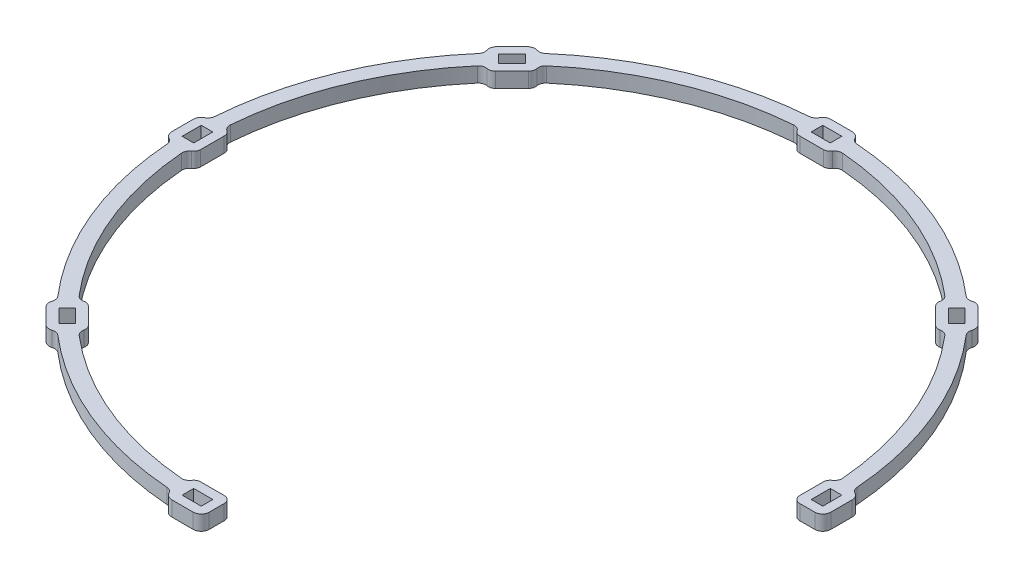
SolidWorks part; units mm, degrees
ref_plane "Front Plane" through (0, 0, 0) normal (0, 0, 1) x (1, 0, 0)
ref_plane "Top Plane" through (0, 0, 0) normal (0, 1, 0) x (1, 0, 0)
ref_plane "Right Plane" through (0, 0, 0) normal (1, 0, 0) x (0, 0, -1)
sketch "Sketch1" plane through (0, 0, 0) normal (0, 1, 0) x (1, 0, 0)
  line L0 (0, 0) -> (2.5, -85.9637) construction
  line L1 (0, 0) -> (85.9637, -2.5) construction
  line L2 (2.3837, -81.9653) -> (2.5, -85.9637)
  line L3 (81.9653, -2.3837) -> (85.9637, -2.5)
  arc A0 (85.9637, -2.5) -> (2.5, -85.9637) centre (0, 0) ccw
  arc A1 (81.9653, -2.3837) -> (2.3837, -81.9653) centre (0, 0) ccw
  dimension "D1" = 172
  dimension "D2" = 4
  dimension "D3" = 2.5
  dimension "D4" = 2.5
extrude "Boss-Extrude1" add sketch "Sketch1" along normal blind 4 contours A1 L2 A0 L3
sketch "Sketch5" plane through (0, 4, 0) normal (0, 1, 0) x (1, 0, 0)
  line L0 (0, -82) -> (0, -86) construction
  line L1 (-61.4104, -54.3393) -> (-64.2439, -57.1728)
  line L2 (-3.1526, -80) -> (3.1526, -80)
  line L3 (-5, -81.8474) -> (-5, -85.8545)
  line L4 (-2.8545, -88) -> (2.8545, -88)
  line L5 (5, -81.8474) -> (5, -85.8545)
  line L6 (-5, -80) -> (5, -88) construction
  line L7 (-5, -88) -> (5, -80) construction
  line L8 (-58.7978, -54.3393) -> (-54.3393, -58.7978)
  line L9 (-54.3393, -61.4104) -> (-57.1728, -64.2439)
  line L10 (-64.2439, -60.2069) -> (-60.2069, -64.2439)
  line L11 (-81.8474, 5) -> (-85.8545, 5)
  line L12 (-80, 3.1526) -> (-80, -3.1526)
  line L13 (-81.8474, -5) -> (-85.8545, -5)
  line L14 (-88, 2.8545) -> (-88, -2.8545)
  line L15 (-54.3393, 61.4104) -> (-57.1728, 64.2439)
  line L16 (-54.3393, 58.7978) -> (-58.7978, 54.3393)
  line L17 (-61.4104, 54.3393) -> (-64.2439, 57.1728)
  line L18 (-60.2069, 64.2439) -> (-64.2439, 60.2069)
  line L19 (5, 81.8474) -> (5, 85.8545)
  line L20 (3.1526, 80) -> (-3.1526, 80)
  line L21 (-5, 81.8474) -> (-5, 85.8545)
  line L22 (2.8545, 88) -> (-2.8545, 88)
  line L23 (61.4104, 54.3393) -> (64.2439, 57.1728)
  line L24 (58.7978, 54.3393) -> (54.3393, 58.7978)
  line L25 (54.3393, 61.4104) -> (57.1728, 64.2439)
  line L26 (64.2439, 60.2069) -> (60.2069, 64.2439)
  line L27 (81.8474, -5) -> (85.8545, -5)
  line L28 (80, -3.1526) -> (80, 3.1526)
  line L29 (81.8474, 5) -> (85.8545, 5)
  line L30 (88, -2.8545) -> (88, 2.8545)
  line L31 (54.3393, -61.4104) -> (57.1728, -64.2439) [skipped]
  line L32 (54.3393, -58.7978) -> (58.7978, -54.3393) [skipped]
  line L33 (61.4104, -54.3393) -> (64.2439, -57.1728) [skipped]
  line L34 (60.2069, -64.2439) -> (64.2439, -60.2069) [skipped]
  line L35 (0, 0) -> (3.1526, -80) construction
  arc A0 (81.9653, -2.3837) -> (2.3837, -81.9653) centre (0, 0) ccw construction
  arc A1 (85.9637, -2.5) -> (2.5, -85.9637) centre (0, 0) ccw construction
  circle A2 centre (0, 0) radius 84 construction
  arc A3 (-5, -85.8545) -> (-2.8545, -88) centre (-2.8545, -85.8545) ccw
  arc A4 (3.1526, -80) -> (5, -81.8474) centre (3.1526, -81.8474) cw
  arc A5 (2.8545, -88) -> (5, -85.8545) centre (2.8545, -85.8545) ccw
  arc A6 (-3.1526, -80) -> (-5, -81.8474) centre (-3.1526, -81.8474) ccw
  arc A7 (-58.7978, -54.3393) -> (-61.4104, -54.3393) centre (-60.1041, -55.6457) ccw
  arc A8 (-64.2439, -57.1728) -> (-64.2439, -60.2069) centre (-62.7268, -58.6899) ccw
  arc A9 (-54.3393, -58.7978) -> (-54.3393, -61.4104) centre (-55.6457, -60.1041) cw
  arc A10 (-60.2069, -64.2439) -> (-57.1728, -64.2439) centre (-58.6899, -62.7268) ccw
  arc A11 (-80, 3.1526) -> (-81.8474, 5) centre (-81.8474, 3.1526) ccw
  arc A12 (-85.8545, 5) -> (-88, 2.8545) centre (-85.8545, 2.8545) ccw
  arc A13 (-80, -3.1526) -> (-81.8474, -5) centre (-81.8474, -3.1526) cw
  arc A14 (-88, -2.8545) -> (-85.8545, -5) centre (-85.8545, -2.8545) ccw
  arc A15 (-54.3393, 58.7978) -> (-54.3393, 61.4104) centre (-55.6457, 60.1041) ccw
  arc A16 (-57.1728, 64.2439) -> (-60.2069, 64.2439) centre (-58.6899, 62.7268) ccw
  arc A17 (-58.7978, 54.3393) -> (-61.4104, 54.3393) centre (-60.1041, 55.6457) cw
  arc A18 (-64.2439, 60.2069) -> (-64.2439, 57.1728) centre (-62.7268, 58.6899) ccw
  arc A19 (3.1526, 80) -> (5, 81.8474) centre (3.1526, 81.8474) ccw
  arc A20 (5, 85.8545) -> (2.8545, 88) centre (2.8545, 85.8545) ccw
  arc A21 (-3.1526, 80) -> (-5, 81.8474) centre (-3.1526, 81.8474) cw
  arc A22 (-2.8545, 88) -> (-5, 85.8545) centre (-2.8545, 85.8545) ccw
  arc A23 (58.7978, 54.3393) -> (61.4104, 54.3393) centre (60.1041, 55.6457) ccw
  arc A24 (64.2439, 57.1728) -> (64.2439, 60.2069) centre (62.7268, 58.6899) ccw
  arc A25 (54.3393, 58.7978) -> (54.3393, 61.4104) centre (55.6457, 60.1041) cw
  arc A26 (60.2069, 64.2439) -> (57.1728, 64.2439) centre (58.6899, 62.7268) ccw
  arc A27 (80, -3.1526) -> (81.8474, -5) centre (81.8474, -3.1526) ccw
  arc A28 (85.8545, -5) -> (88, -2.8545) centre (85.8545, -2.8545) ccw
  arc A29 (80, 3.1526) -> (81.8474, 5) centre (81.8474, 3.1526) cw
  arc A30 (88, 2.8545) -> (85.8545, 5) centre (85.8545, 2.8545) ccw
  arc A31 (54.3393, -58.7978) -> (54.3393, -61.4104) centre (55.6457, -60.1041) ccw [skipped]
  arc A32 (57.1728, -64.2439) -> (60.2069, -64.2439) centre (58.6899, -62.7268) ccw [skipped]
  arc A33 (58.7978, -54.3393) -> (61.4104, -54.3393) centre (60.1041, -55.6457) cw [skipped]
  arc A34 (64.2439, -60.2069) -> (64.2439, -57.1728) centre (62.7268, -58.6899) ccw [skipped]
  arc A38 (85.9637, -2.5) -> (2.5, -85.9637) centre (0, 0) ccw construction
  arc A39 (81.8474, 5) -> (2.3837, -81.9653) centre (0, 0) ccw construction
  point P12 (0, -84)
  point P13 (0, -84)
  dimension "D3" = 8
  dimension "D1" = 8
  dimension "D2" = 10
extrude "Boss-Extrude2" add sketch "Sketch5" against normal up to surface (4 mm away) up to face at (-8.0969, 0, -8.0969)
sketch "Sketch3" plane through (0, 4, 0) normal (0, 1, 0) x (1, 0, 0)
  line L0 (-62.2961, -58.6899) -> (-58.6899, -62.2961)
  line L1 (-2.55, -82.45) -> (2.55, -82.45)
  line L2 (-2.55, -82.45) -> (-2.55, -85.55)
  line L3 (-2.55, -85.55) -> (2.55, -85.55)
  line L4 (2.55, -82.45) -> (2.55, -85.55)
  line L5 (-2.55, -82.45) -> (2.55, -85.55) construction
  line L6 (-2.55, -85.55) -> (2.55, -82.45) construction
  line L7 (-56.4978, -60.1041) -> (-58.6899, -62.2961)
  line L8 (-60.1041, -56.4978) -> (-56.4978, -60.1041)
  line L9 (-60.1041, -56.4978) -> (-62.2961, -58.6899)
  line L10 (-85.55, 2.55) -> (-85.55, -2.55)
  line L11 (-82.45, -2.55) -> (-85.55, -2.55)
  line L12 (-82.45, 2.55) -> (-82.45, -2.55)
  line L13 (-82.45, 2.55) -> (-85.55, 2.55)
  line L14 (-58.6899, 62.2961) -> (-62.2961, 58.6899)
  line L15 (-60.1041, 56.4978) -> (-62.2961, 58.6899)
  line L16 (-56.4978, 60.1041) -> (-60.1041, 56.4978)
  line L17 (-56.4978, 60.1041) -> (-58.6899, 62.2961)
  line L18 (2.55, 85.55) -> (-2.55, 85.55)
  line L19 (-2.55, 82.45) -> (-2.55, 85.55)
  line L20 (2.55, 82.45) -> (-2.55, 82.45)
  line L21 (2.55, 82.45) -> (2.55, 85.55)
  line L22 (62.2961, 58.6899) -> (58.6899, 62.2961)
  line L23 (56.4978, 60.1041) -> (58.6899, 62.2961)
  line L24 (60.1041, 56.4978) -> (56.4978, 60.1041)
  line L25 (60.1041, 56.4978) -> (62.2961, 58.6899)
  line L26 (85.55, -2.55) -> (85.55, 2.55)
  line L27 (82.45, 2.55) -> (85.55, 2.55)
  line L28 (82.45, -2.55) -> (82.45, 2.55)
  line L29 (82.45, -2.55) -> (85.55, -2.55)
  line L30 (58.6899, -62.2961) -> (62.2961, -58.6899) [skipped]
  line L31 (60.1041, -56.4978) -> (62.2961, -58.6899) [skipped]
  line L32 (56.4978, -60.1041) -> (60.1041, -56.4978) [skipped]
  line L33 (56.4978, -60.1041) -> (58.6899, -62.2961) [skipped]
  line L34 (0, 0) -> (2.55, -82.45) construction
  point P0 (0, -84)
  dimension "D1" = 5.1
  dimension "D2" = 3.1
  dimension "D3" = 8
extrude "Cut-Extrude1" cut sketch "Sketch3" against normal up to next
fillet "Fillet1" radius 2 24 edges at (54.3393, 2, -61.4104) (64.2439, 2, -57.1728) (61.4104, 2, -54.3393) (57.1728, 2, -64.2439) (-5, 2, 85.8545) (-5, 2, -81.8474) (5, 2, -81.8474) (-61.4104, 2, -54.3393) (-54.3393, 2, -61.4104) (-81.8474, 2, -5) (-81.8474, 2, 5) (-64.2439, 2, 57.1728) (-57.1728, 2, 64.2439) (-54.3393, 2, 61.4104) (-85.8545, 2, 5) (5, 2, -85.8545) (-64.2439, 2, -57.1728) (-5, 2, 81.8474) (-61.4104, 2, 54.3393) (-85.8545, 2, -5) (-57.1728, 2, -64.2439) (-5, 2, -85.8545) (81.8474, 2, -5) (85.8545, 2, -5)
